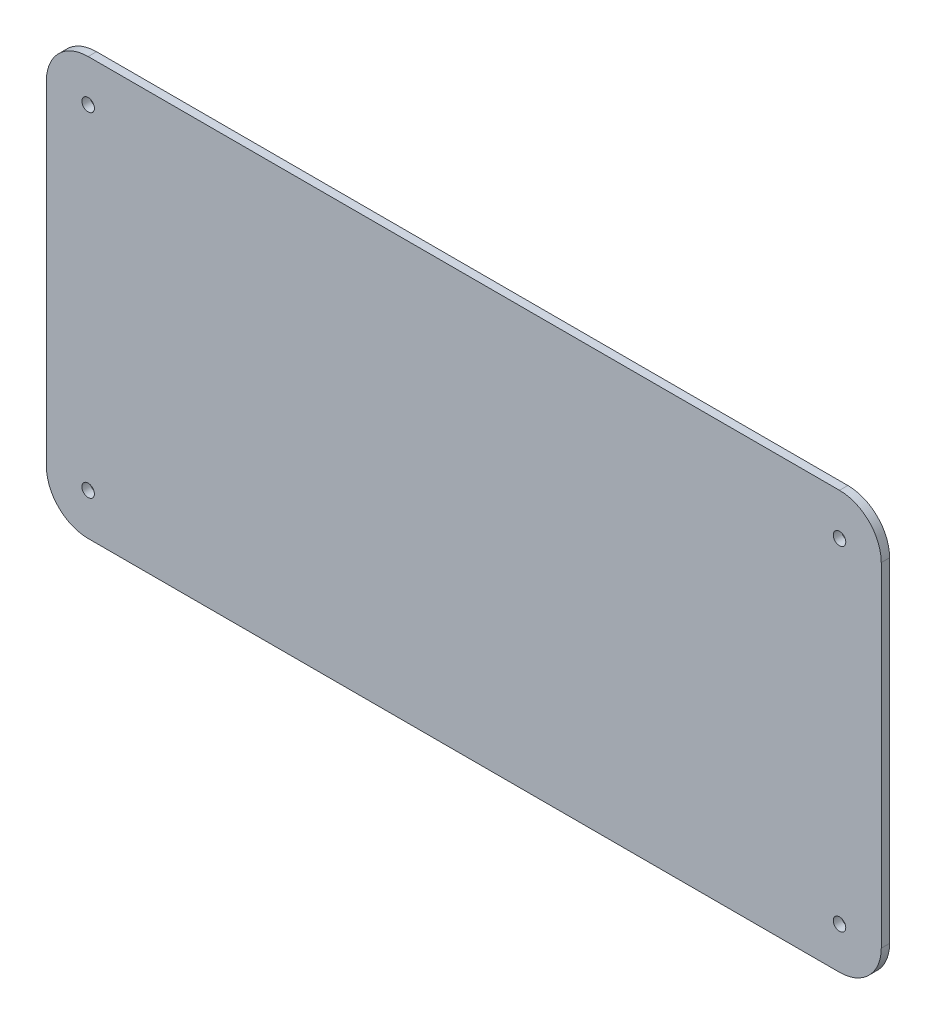
SolidWorks part; units mm, degrees
ref_plane "Front Plane" through (0, 0, 0) normal (0, 0, 1) x (1, 0, 0)
ref_plane "Top Plane" through (0, 0, 0) normal (0, 1, 0) x (1, 0, 0)
ref_plane "Right Plane" through (0, 0, 0) normal (1, 0, 0) x (0, 0, -1)
sketch "Sketch1" plane through (0, 0, 0) normal (0, 0, 1) x (1, 0, 0)
  line L0 (-108.5207, 55.7591) -> (-108.5207, 27.0091)
  line L1 (-98.5207, -34.2409) -> (81.4745, -34.2409)
  line L2 (91.4745, 55.7591) -> (91.4745, 27.0091)
  line L7 (-108.5207, 4.5091) -> (-108.5207, -24.2409)
  line L12 (91.4745, 4.5091) -> (91.4745, -24.2409)
  line L13 (-98.5207, 65.7591) -> (81.4745, 65.7591)
  line L14 (-108.5207, 27.0091) -> (-108.5207, 4.5091)
  line L15 (91.4745, 4.5091) -> (91.4745, 27.0091)
  line L16 (111.4745, 55.7591) -> (111.4745, 27.0091)
  line L17 (111.4745, 4.5091) -> (111.4745, 27.0091)
  line L18 (111.4745, 4.5091) -> (111.4745, -24.2409)
  line L19 (-98.5207, -54.2409) -> (81.4745, -54.2409)
  line L20 (-128.5207, 4.5091) -> (-128.5207, -24.2409)
  line L21 (-128.5207, 27.0091) -> (-128.5207, 4.5091)
  line L22 (-128.5207, 55.7591) -> (-128.5207, 27.0091)
  line L23 (-98.5207, 85.7591) -> (81.4745, 85.7591)
  arc A0 (-108.5207, -24.2409) -> (-98.5207, -34.2409) centre (-98.5207, -24.2409) ccw
  arc A1 (81.4745, -34.2409) -> (91.4745, -24.2409) centre (81.4745, -24.2409) ccw
  arc A2 (81.4745, 65.7591) -> (91.4745, 55.7591) centre (81.4745, 55.7591) cw
  arc A3 (-98.5207, 65.7591) -> (-108.5207, 55.7591) centre (-98.5207, 55.7591) ccw
  circle A4 centre (-98.5207, 55.7591) radius 1.5
  circle A5 centre (-98.5207, -24.2409) radius 1.5
  circle A6 centre (81.4745, -24.2409) radius 1.5
  circle A7 centre (81.4745, 55.7591) radius 1.5
  arc A8 (81.4745, -54.2409) -> (111.4745, -24.2409) centre (81.4745, -24.2409) ccw
  arc A9 (-128.5207, -24.2409) -> (-98.5207, -54.2409) centre (-98.5207, -24.2409) ccw
  arc A10 (-98.5207, 85.7591) -> (-128.5207, 55.7591) centre (-98.5207, 55.7591) ccw
  arc A11 (81.4745, 85.7591) -> (111.4745, 55.7591) centre (81.4745, 55.7591) cw
  dimension "D1" = 20
extrude "Boss-Extrude1" add sketch "Sketch1" along normal blind 2 contours L2 L15 L12 A1 L1 A0 L7 L14 L0 A3 L13 A2 | A7 | A6 | A5 | A4
